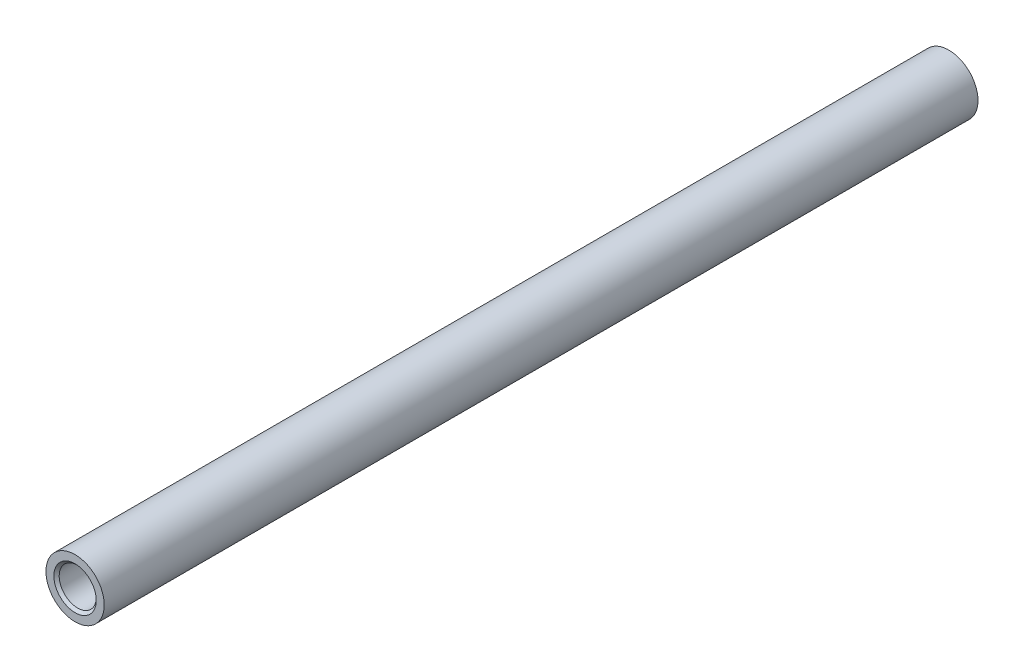
SolidWorks part; units mm, degrees
material "1.0545 (S355N)"
ref_plane "Płaszczyzna przednia" through (0, 0, 0) normal (0, 0, 1) x (1, 0, 0)
ref_plane "Płaszczyzna górna" through (0, 0, 0) normal (0, 1, 0) x (1, 0, 0)
ref_plane "Płaszczyzna prawa" through (0, 0, 0) normal (1, 0, 0) x (0, 0, -1)
sketch "Szkic1" plane through (0, 0, 0) normal (0, 0, 1) x (1, 0, 0)
  circle A0 centre (0, 0) radius 11
  circle A1 centre (0, 0) radius 7
  dimension "D1" = 22
  dimension "D2" = 4
extrude "Dodanie-wyciągnięcie1" add sketch "Szkic1" along normal mid plane 330
sketch "Szkic2" plane through (0, 0, -165) normal (0, 0, -1) x (-1, 0, 0)
  circle A0 centre (0, 0) radius 8
  circle A1 centre (0, 0) radius 7 construction
  dimension "D1" = 1
extrude "Wytnij-wyciągnięcie1" cut sketch "Szkic2" against normal blind 50
chamfer "Sfazowanie1" distance 1 angle 45 1 edges at (7, 0, 165)
